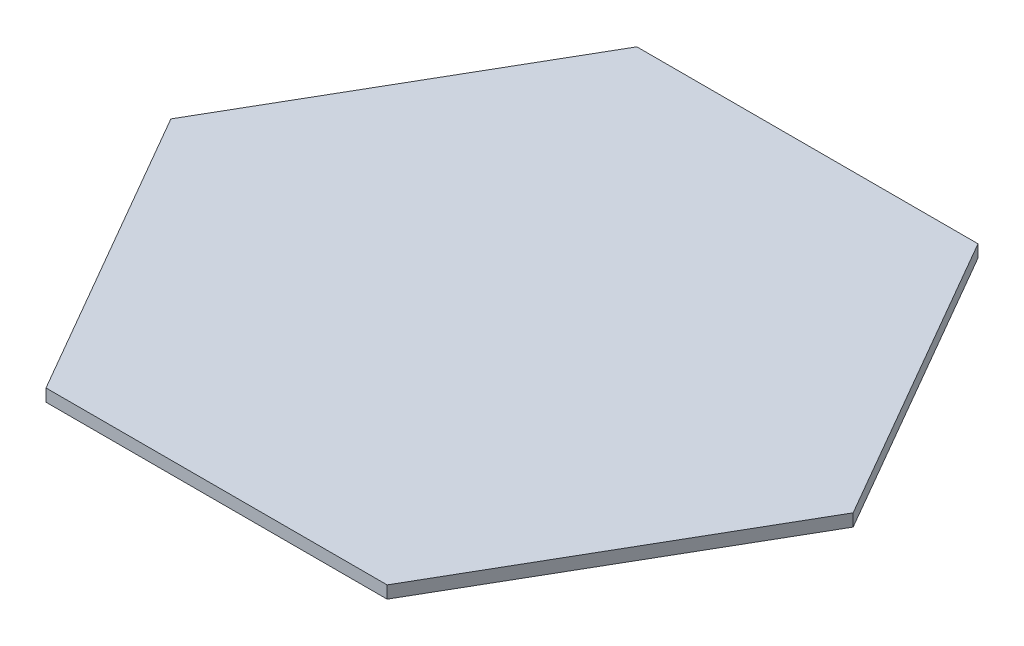
SolidWorks part; units mm, degrees
material "1023 Carbon Steel Sheet (SS)"
ref_plane "Front Plane" through (0, 0, 0) normal (0, 0, 1) x (1, 0, 0)
ref_plane "Top Plane" through (0, 0, 0) normal (0, 1, 0) x (1, 0, 0)
ref_plane "Right Plane" through (0, 0, 0) normal (1, 0, 0) x (0, 0, -1)
sketch "Sketch1" plane through (0, 0, 0) normal (0, 1, 0) x (1, 0, 0)
  line L1 (137.8868, 0) -> (68.9434, 119.4134)
  line L2 (68.9434, 119.4134) -> (-68.9434, 119.4134)
  line L3 (-68.9434, 119.4134) -> (-137.8868, 0)
  line L4 (-137.8868, 0) -> (-68.9434, -119.4134)
  line L5 (-68.9434, -119.4134) -> (68.9434, -119.4134)
  line L6 (68.9434, -119.4134) -> (137.8868, 0)
  line L7 (135, 0) -> (67.5, 116.9134) construction
  line L8 (67.5, 116.9134) -> (-67.5, 116.9134) construction
  line L9 (-67.5, 116.9134) -> (-135, 0) construction
  line L10 (-135, 0) -> (-67.5, -116.9134) construction
  line L11 (-67.5, -116.9134) -> (67.5, -116.9134) construction
  line L12 (67.5, -116.9134) -> (135, 0) construction
  circle A0 centre (0, 0) radius 119.4134 construction
  circle A1 centre (0, 0) radius 116.9134 construction
  dimension "D1" = 2.5
  dimension "D2" = 135
extrude "Boss-Extrude1" add sketch "Sketch1" along normal blind 5
